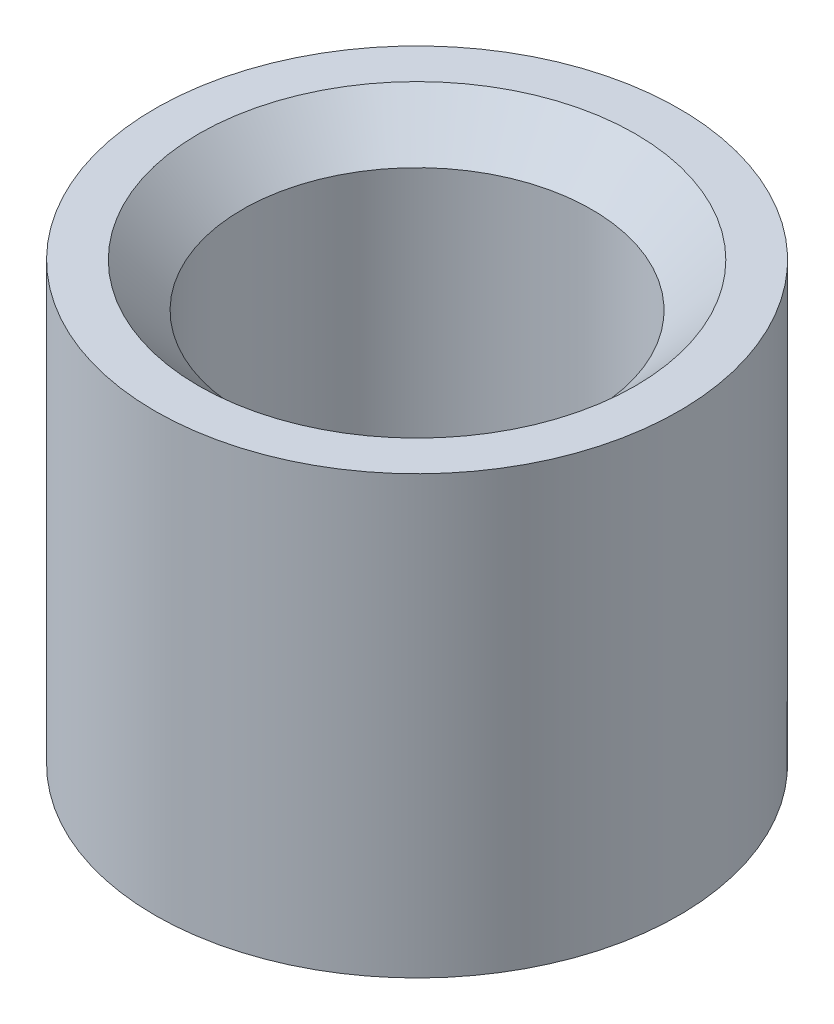
SolidWorks part; units mm, degrees
material "Bronzo commerciale, UNS C22000 (Bronzo 90-10)"
ref_plane "Front" through (0, 0, 0) normal (0, 0, 1) x (1, 0, 0)
ref_plane "Top" through (0, 0, 0) normal (0, 1, 0) x (1, 0, 0)
ref_plane "Right" through (0, 0, 0) normal (1, 0, 0) x (0, 0, -1)
sketch "Schizzo1" plane through (0, 0, 0) normal (0, 1, 0) x (1, 0, 0)
  circle A0 centre (0, 0) radius 6
  circle A1 centre (0, 0) radius 4
  dimension "D1" = 12
  dimension "D2" = 8
extrude "Estrusione-Estrusione1" add sketch "Schizzo1" along normal blind 10
chamfer "Smusso1" distance 1 angle 45 1 edges at (0, 10, 4)
